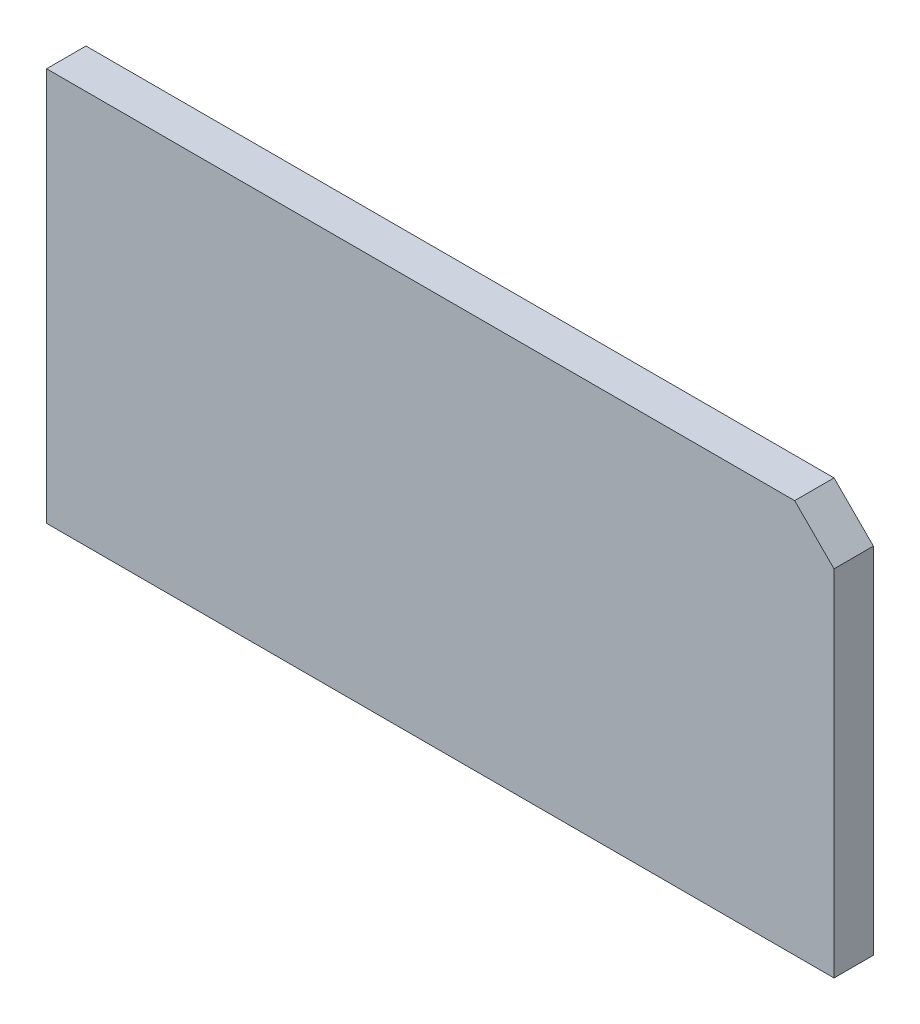
SolidWorks part; units mm, degrees
ref_plane "Front Plane" through (0, 0, 0) normal (0, 0, 1) x (1, 0, 0)
ref_plane "Top Plane" through (0, 0, 0) normal (0, 1, 0) x (1, 0, 0)
ref_plane "Right Plane" through (0, 0, 0) normal (1, 0, 0) x (0, 0, -1)
sketch "Sketch1" plane through (0, 0, 0) normal (0, 0, 1) x (1, 0, 0)
  line L1 (-1000, 500) -> (1000, 500)
  line L2 (-1000, 500) -> (-1000, -500)
  line L3 (-1000, -500) -> (1000, -500)
  line L4 (1000, 500) -> (1000, -500)
  dimension "table_width" = 1000
  dimension "table_length" = 2000
  dimension "D1" = 1000
  dimension "D2" = 500
extrude "Boss-Extrude1" add sketch "Sketch1" against normal blind 100
sketch "Sketch2" plane through (0, 0, 0) normal (0, 0, 1) x (1, 0, 0)
  line L0 (900, 500) -> (1000, 400)
  line L1 (1000, 500) -> (-1000, 500) construction
  line L2 (1000, -500) -> (1000, 500) construction
  line L3 (1000, 400) -> (1000, 500)
  line L4 (1000, 500) -> (900, 500)
  dimension "D1" = 45
  dimension "D2" = 100
extrude "Cut-Extrude1" cut sketch "Sketch2" against normal blind 200
equation "\"D1@Sketch1\"=\"table_length@Sketch1\"/2"
equation "\"D2@Sketch1\"=\"table_width@Sketch1\"/2"
